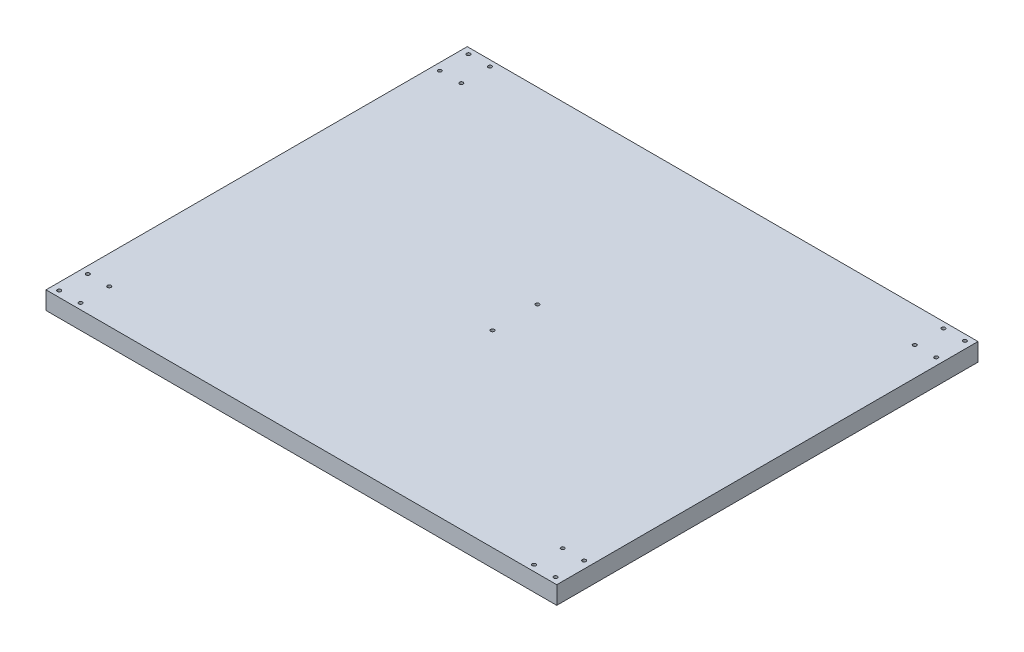
SolidWorks part; units mm, degrees
ref_plane "Alzado" through (0, 0, 0) normal (0, 0, 1) x (1, 0, 0)
ref_plane "Planta" through (0, 0, 0) normal (0, 1, 0) x (1, 0, 0)
ref_plane "Vista lateral" through (0, 0, 0) normal (1, 0, 0) x (0, 0, -1)
sketch "Croquis1" plane through (0, 0, 0) normal (0, 1, 0) x (1, 0, 0)
  line L0 (0, -176.5) -> (0, 176.5) construction
  line L1 (-214, -176.5) -> (214, -176.5)
  line L2 (-214, -176.5) -> (-214, 176.5)
  line L3 (-214, 176.5) -> (214, 176.5)
  line L4 (214, -176.5) -> (214, 176.5)
  line L5 (-214, -176.5) -> (214, 176.5) construction
  line L6 (-214, 176.5) -> (214, -176.5) construction
  circle A2 centre (2.5, 18.8) radius 1.5
  circle A3 centre (2.5, -18.8) radius 1.5
  point P0 (0, 0)
  dimension "D6" = 3
  dimension "D1" = 428
  dimension "D2" = 353
  dimension "D7" = 2.5
  dimension "D8" = 18.8
  dimension "D9" = 18.8
extrude "Saliente-Extruir1" add sketch "Croquis1" along normal blind 15
sketch "Croquis2" plane through (0, 15, 0) normal (0, 1, 0) x (1, 0, 0)
  line L0 (0, 176.5) -> (0, -176.5) construction
  line L1 (214, 176.5) -> (-214, 176.5) construction
  line L2 (-214, -176.5) -> (214, -176.5) construction
  line L3 (-176.5, 176.5) -> (-176.5, -176.5) construction
  line L4 (176.5, 176.5) -> (176.5, -176.5) construction
  line L5 (-214, 0) -> (214, 0) construction
  line L6 (-214, 176.5) -> (-214, -176.5) construction
  line L7 (214, -176.5) -> (214, 176.5) construction
  dimension "D1" = 176.5
  dimension "D2" = 176.5
sketch "Croquis3" plane through (0, 15, 0) normal (0, 1, 0) x (1, 0, 0)
  line L0 (-214, -176.5) -> (214, -176.5) construction
  line L1 (214, -176.5) -> (214, 176.5) construction
  line L2 (0, 176.5) -> (0, -176.5) construction
  line L3 (-214, 0) -> (214, 0) construction
  circle A0 centre (208, -171.5) radius 1.5
  circle A1 centre (190, -171.5) radius 1.5
  circle A2 centre (190, -147.5) radius 1.5
  circle A3 centre (208, -147.5) radius 1.5
  circle A4 centre (-208, -171.5) radius 1.5
  circle A5 centre (-190, -171.5) radius 1.5
  circle A6 centre (-208, -147.5) radius 1.5
  circle A7 centre (-190, -147.5) radius 1.5
  circle A8 centre (-208, 171.5) radius 1.5
  circle A9 centre (-190, 171.5) radius 1.5
  circle A10 centre (-190, 147.5) radius 1.5
  circle A11 centre (-208, 147.5) radius 1.5
  circle A12 centre (208, 171.5) radius 1.5
  circle A13 centre (190, 171.5) radius 1.5
  circle A14 centre (190, 147.5) radius 1.5
  circle A15 centre (208, 147.5) radius 1.5
  dimension "D1" = 3
  dimension "D2" = 24
  dimension "D3" = 5
  dimension "D4" = 6
  dimension "D5" = 18
extrude "Cortar-Extruir1" cut sketch "Croquis3" against normal through all
